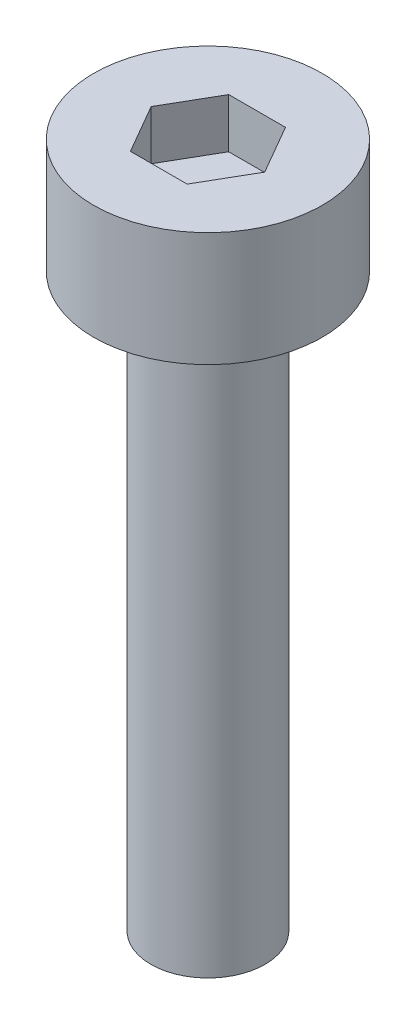
SolidWorks part; units mm, degrees
ref_plane "Front Plane" through (0, 0, 0) normal (0, 0, 1) x (1, 0, 0)
ref_plane "Top Plane" through (0, 0, 0) normal (0, 1, 0) x (1, 0, 0)
ref_plane "Right Plane" through (0, 0, 0) normal (1, 0, 0) x (0, 0, -1)
sketch "Sketch1" plane through (0, 0, 0) normal (0, 1, 0) x (1, 0, 0)
  circle A0 centre (0, 0) radius 1.5
  dimension "D1" = 3
extrude "ScrewShaft" add sketch "Sketch1" along normal blind 15
sketch "Sketch2" plane through (0, 15, 0) normal (0, 1, 0) x (1, 0, 0)
  circle A0 centre (0, 0) radius 3
  dimension "D1" = 6
extrude "Boss-Extrude2" add sketch "Sketch2" along normal blind 3
sketch "Sketch3" plane through (0, 18, 0) normal (0, 1, 0) x (1, 0, 0)
  line L0 (0, 0) -> (0, 1.29) construction
  line L1 (1.4896, 0) -> (0.7448, 1.29)
  line L2 (0.7448, 1.29) -> (-0.7448, 1.29)
  line L3 (-0.7448, 1.29) -> (-1.4896, 0)
  line L4 (-1.4896, 0) -> (-0.7448, -1.29)
  line L5 (-0.7448, -1.29) -> (0.7448, -1.29)
  line L6 (0.7448, -1.29) -> (1.4896, 0)
  circle A0 centre (0, 0) radius 1.29 construction
  dimension "D1" = 2.58
extrude "Cut-Extrude1" cut sketch "Sketch3" against normal blind 1.3
equation "\"X-ROD-SPACING\"=45"
equation "\"Y-ROD-SPACING\"=75"
equation "\"Z-ROD-SPACING\"=17.5"
equation "\"Y-BED-OFFSET\"=2"
equation "\"Y-BED-ROD-INSET\"=3.5"
equation "\"T-SLOT-NUT-FILLET-RADIUS\"=0.5"
equation "\"T-SLOT-SCREW-SHAFT-RADIUS\"=1.55"
equation "\"T-SLOT-SCREW-SHAFT-CUTOUT-LENGTH\"=11.0"
equation "\"T-SLOT-NUT-DEPTH\"=3.5"
equation "\"T-SLOT-NUT-WIDTH\"=2.85"
equation "\"T-SLOT-NUT-END-DISTANCE\"=8"
equation "\"ACRYLIC-THICKNESS\"=10"
equation "\"ACRYLIC-THICKNESS2\"=4.5"
equation "\"ACRYLIC-TAB-CUTOUT-SIZE\"=\"ACRYLIC-THICKNESS\"+\"ACRYLIC-TAB-TOLERANCE\"*2"
equation "\"ACRYLIC-TAB-WIDTH\"=\"ACRYLIC-THICKNESS\""
equation "\"ACRYLIC-M3-HOLE\"=2.9"
equation "\"SMOOTHROD-CAP-SCREW-DISTANCE\"=20"
equation "\"FRAME-WIDTH-INNER\"=370"
equation "\"NEMA17-HOLE-SPACING\"=31"
equation "\"NEMA17-CENTRAL-CUTOUT\"=22.5"
equation "\"Z-BRACKET-REACH\"=55"
equation "\"TOP-BRACKET-SPACING\"=40"
equation "\"SMOOTHROD-X-LENGTH\"=350"
equation "\"SMOOTHROD-Y-LENGTH\"=350"
equation "\"SMOOTHROD-Z-LENGTH\"=350"
equation "\"SMOOTHROD-TIGHTENING-HEADROOM\"=.25"
equation "\"LEADSCREW-Z-LENGTH\"=300"
equation "\"SCREW-LENGTH-FRAME\"=\"ACRYLIC-THICKNESS\" + 10"
equation "\"SCREW-HEAD-RADIUS\"=6"
equation "\"PRINTED-X-SMOOTHROD-DIAMETER\"=8.4"
equation "\"PRINTED-X-SMOOTHROD-CUTOUT\"=10"
equation "\"PRINTED-X-BASE-HEIGHT\"=10"
equation "\"PRINTED-LM8UU-CUTOUT-SIZE\"=15.5"
equation "\"PRINTED-LM8UU-CUTOUT-LENGTH\"=24.5"
equation "\"PRINTED-X-IDLER-HEIGHT\"=16"
equation "\"PSU-MOUNTING-WIDTH\"=95"
equation "\"PSU-MOUNTING-HEIGHT\"=177"
equation "\"D1@ScrewShaft\"=\"SCREW-LENGTH-MOTOR\""
equation "\"D1@Sketch2\"=\"SCREW-HEAD-RADIUS\""
equation "\"Y-BED-SCREW-SPACING\"=209"
equation "\"Y-BED-SCREW-CUTOUT-SLOT-HEIGHT\"=2"
equation "\"Z-ROD-INSET\"=16"
equation "\"SCREW-LENGTH-MOTOR\"=\"ACRYLIC-THICKNESS\" + 5"
equation "\"Y-BELT-TO-ROD-DISTANCE\"=20"
equation "\"SPOOL-HOLDER-ROD-SPACING\"=150"
